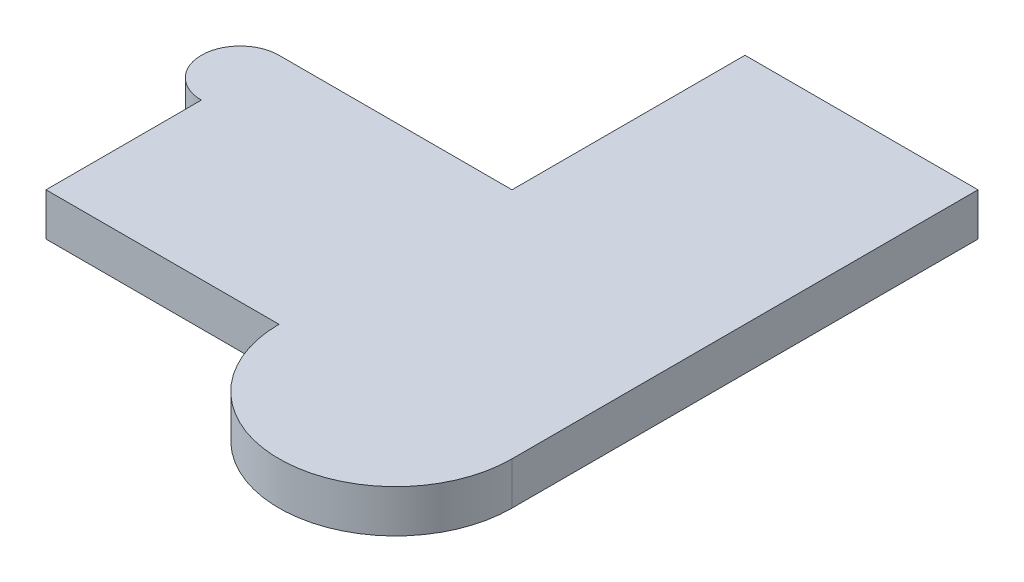
SolidWorks part; units mm, degrees
ref_plane "Front Plane" through (0, 0, 0) normal (0, 0, 1) x (1, 0, 0)
ref_plane "Top Plane" through (0, 0, 0) normal (0, 1, 0) x (1, 0, 0)
ref_plane "Right Plane" through (0, 0, 0) normal (1, 0, 0) x (0, 0, -1)
sketch "aula 4" plane through (0, 0, 0) normal (0, 1, 0) x (1, 0, 0)
  line L0 (0, 0) -> (0, 60)
  line L1 (0, 60) -> (60, 60)
  line L2 (60, 60) -> (60, -60)
  line L3 (0, -60) -> (-60, -60)
  line L4 (-60, -60) -> (-60, -20)
  line L5 (-60, 0) -> (0, 0)
  arc A0 (60, -60) -> (0, -60) centre (30, -60) cw
  arc A1 (-60, -20) -> (-60, 0) centre (-60, -10) cw
  dimension "D5" = 60
  dimension "D1" = 30
  dimension "D2" = 10
  dimension "D3" = 60
  dimension "D4" = 60
extrude "Boss-Extrude2" add sketch "aula 4" along normal blind 11
